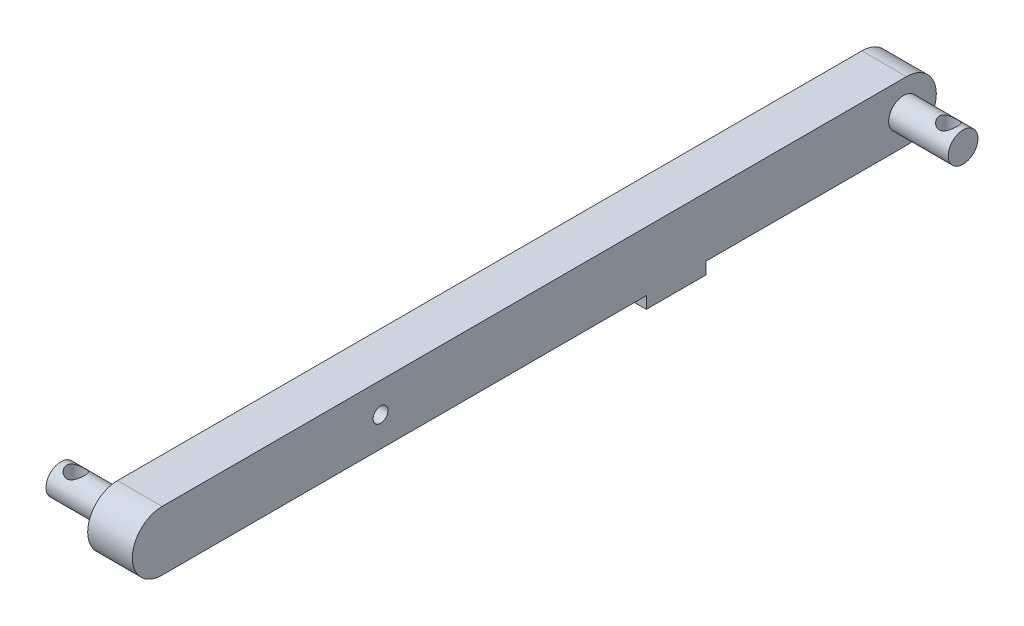
SolidWorks part; units mm, degrees
material "Oak"
ref_plane "Front Plane" through (0, 0, 0) normal (0, 0, 1) x (1, 0, 0)
ref_plane "Top Plane" through (0, 0, 0) normal (0, 1, 0) x (1, 0, 0)
ref_plane "Right Plane" through (0, 0, 0) normal (1, 0, 0) x (0, 0, -1)
sketch "Sketch2" plane through (0, 0, 0) normal (1, 0, 0) x (0, 0, -1)
  line L1 (-158.75, 12.7) -> (158.75, 12.7)
  line L3 (-158.75, -12.7) -> (158.75, -12.7)
  line L5 (-158.75, 12.7) -> (158.75, -12.7) construction
  line L6 (-158.75, -12.7) -> (158.75, 12.7) construction
  arc A0 (158.75, 12.7) -> (158.75, -12.7) centre (158.75, 0) cw
  arc A1 (-158.75, 12.7) -> (-158.75, -12.7) centre (-158.75, 0) ccw
  point P0 (0, 0)
  dimension "D1" = 25.4
  dimension "D2" = 317.5
extrude "Boss-Extrude1" add sketch "Sketch2" along normal mid plane 19.05
sketch "Sketch4" plane through (-9.525, 0, 0) normal (-1, 0, 0) x (0, 0, 1)
  line L0 (171.45, 0) -> (157.48, 0) construction
  circle A0 centre (157.48, 0) radius 6.35
  arc A1 (158.75, -12.7) -> (158.75, 12.7) centre (158.75, 0) ccw construction
  dimension "D2" = 12.7
  dimension "D1" = 13.97
extrude "Boss-Extrude2" add sketch "Sketch4" along normal blind 25.4
sketch "Sketch5" plane through (9.525, 0, 0) normal (1, 0, 0) x (0, 0, -1)
  line L0 (171.45, 0) -> (157.48, 0) construction
  circle A0 centre (157.48, 0) radius 6.35
  arc A1 (158.75, -12.7) -> (158.75, 12.7) centre (158.75, 0) ccw construction
  dimension "D2" = 12.7
  dimension "D1" = 13.97
extrude "Boss-Extrude3" add sketch "Sketch5" along normal blind 25.4
sketch "Sketch6" plane through (9.525, 0, 0) normal (1, 0, 0) x (0, 0, -1)
  line L0 (-171.45, 0) -> (-65.6082, 0) construction
  circle A0 centre (-65.6082, 0) radius 3.175
  arc A1 (-158.75, 12.7) -> (-158.75, -12.7) centre (-158.75, 0) ccw construction
  dimension "D1" = 6.35
  dimension "D2" = 105.8418
extrude "Cut-Extrude1" cut sketch "Sketch6" against normal up to surface (19.05 mm away) up to face at (-9.525, 0, 163.83)
sketch "Sketch7" plane through (0, -12.7, 0) normal (0, -1, 0) x (1, 0, 0)
  line L0 (-9.525, 158.75) -> (-9.525, -158.75) construction
  line L1 (-9.525, -47.752) -> (9.525, -47.752)
  line L2 (-9.525, -47.752) -> (-9.525, -73.152)
  line L3 (-9.525, -73.152) -> (9.525, -73.152)
  line L4 (9.525, -47.752) -> (9.525, -73.152)
  line L5 (9.525, 158.75) -> (9.525, -158.75) construction
  line L6 (9.525, -158.75) -> (-9.525, -158.75) construction
  point P10 (0, -158.75)
  dimension "D1" = 25.4
  dimension "D2" = 110.998
extrude "Boss-Extrude4" add sketch "Sketch7" along normal blind 5.08
sketch "Sketch8" plane through (0, 0, 0) normal (0, 1, 0) x (1, 0, 0)
  line L0 (-34.925, -157.48) -> (-9.525, -157.48) construction
  line L1 (-34.925, -151.13) -> (-34.925, -163.83) construction
  line L2 (-9.525, 158.75) -> (-9.525, -158.75) construction
  line L3 (-9.525, -151.13) -> (-9.525, -163.83) construction
  line L4 (9.525, 157.48) -> (34.925, 157.48) construction
  line L5 (9.525, 151.13) -> (9.525, 163.83) construction
  line L6 (34.925, 151.13) -> (34.925, 163.83) construction
  circle A0 centre (-28.575, -157.48) radius 3.81
  circle A1 centre (28.575, 157.48) radius 3.81
  dimension "D1" = 7.62
  dimension "D3" = 7.62
  dimension "D2" = 19.05
  dimension "D4" = 19.05
extrude "Cut-Extrude2" cut sketch "Sketch8" against normal mid plane 12.7
